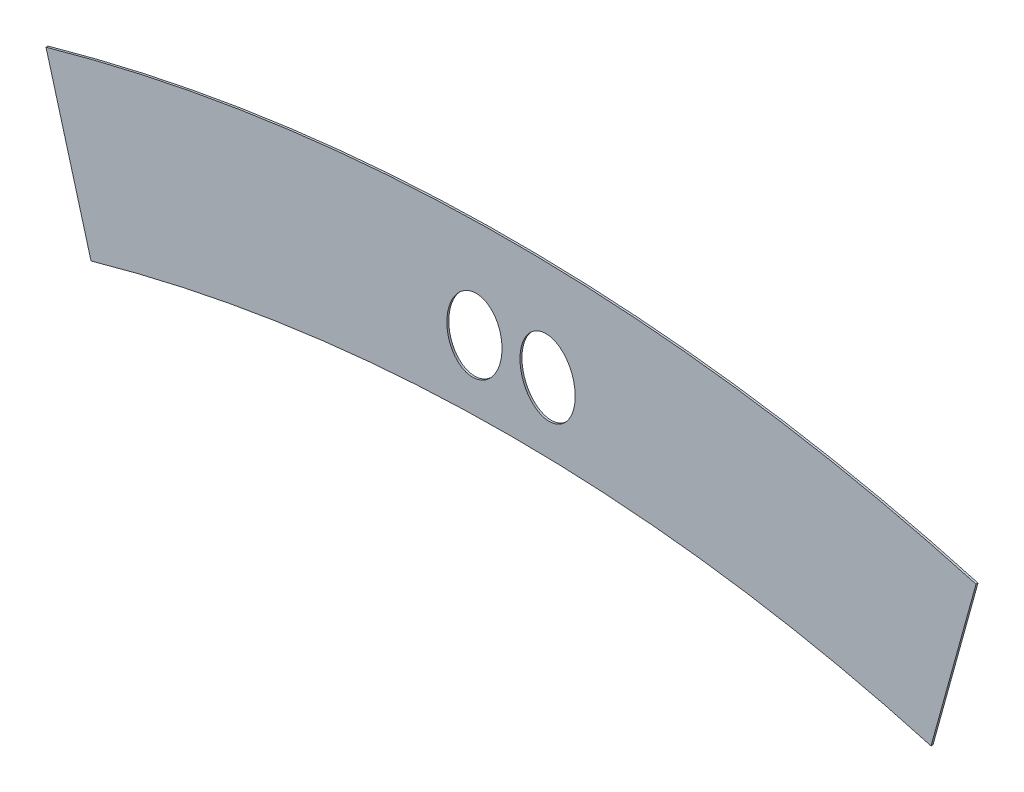
SolidWorks part; units mm, degrees
material "6061 Alloy"
ref_plane "front" through (0, 0, 0) normal (0, 0, 1) x (1, 0, 0)
ref_plane "top" through (0, 0, 0) normal (0, 1, 0) x (1, 0, 0)
ref_plane "right" through (0, 0, 0) normal (1, 0, 0) x (0, 0, -1)
sketch "Sketch1" plane through (0, 0, 0) normal (0, 0, 1) x (1, 0, 0)
  line L0 (0, 0) -> (0, -273.05) construction
  line L1 (0, 0) -> (383.281, 0) construction
  line L2 (-752.475, -104.363) -> (-679.6278, -367.5211)
  line L3 (752.475, -104.363) -> (679.6278, -367.5211)
  line L4 (-42.8625, -0.3323) -> (-70.6176, -274.0508) construction
  line L5 (42.8625, -0.3323) -> (70.6176, -274.0508) construction
  arc A0 (752.475, -104.363) -> (-752.475, -104.363) centre (0, -2764.917) ccw
  arc A1 (679.6278, -367.5211) -> (-679.6278, -367.5211) centre (0, -2764.917) ccw
  ellipse E0 centre (-59.1979, -161.4312) end of major axis (-65.2837, -221.4484) minor radius 44.45
  ellipse E1 centre (59.1979, -161.4312) end of major axis (65.2837, -221.4484) minor radius 44.45
  dimension "D1" = 2764.917
  dimension "D5" = 5.79
  dimension "D7" = 88.9
  dimension "D2" = 1504.95
  dimension "D3" = 273.05
  dimension "D4" = 679.6278
  dimension "D6" = 42.8625
  dimension "D8" = 120.65
  dimension "D9" = 161.925
  dimension "D11" = 752.475
  dimension "D13" = 679.6278
extrude "Base-Extrude" add sketch "Sketch1" against normal blind 3.175
